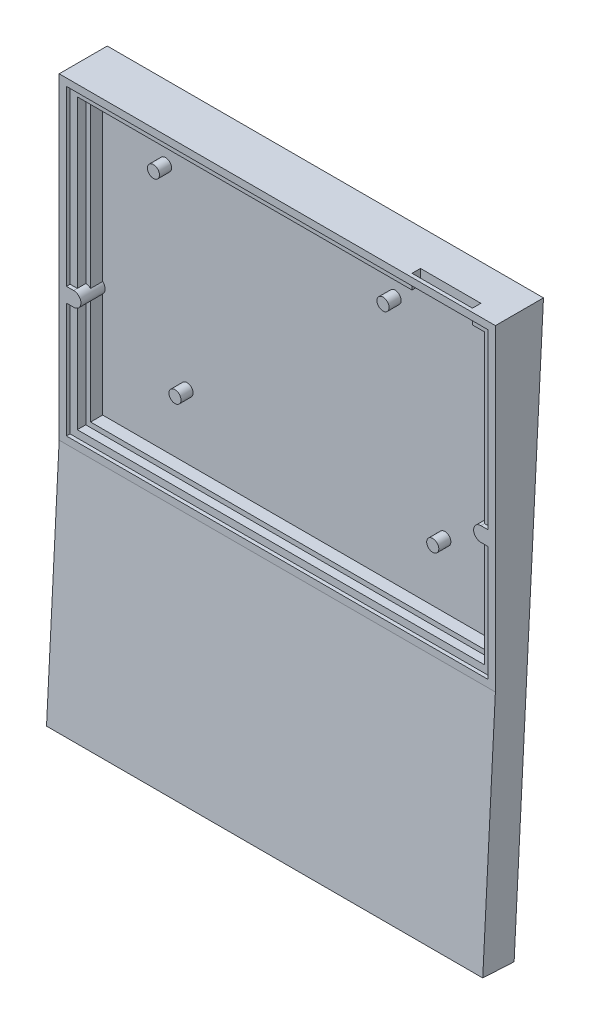
SolidWorks part; units mm, degrees
ref_plane "前视基准面" through (0, 0, 0) normal (0, 0, 1) x (1, 0, 0)
ref_plane "上视基准面" through (0, 0, 0) normal (0, 1, 0) x (1, 0, 0)
ref_plane "右视基准面" through (0, 0, 0) normal (1, 0, 0) x (0, 0, -1)
sketch "Model" plane through (0, 0, 0) normal (0, 0, 1) x (1, 0, 0)
  line L0 (565.3976, -76.1053) -> (390.8957, -76.1053)
  line L1 (390.8957, -76.1053) -> (390.8957, -28.4789)
  line L2 (390.8957, -22.4789) -> (390.8957, 49.195)
  line L3 (390.8957, 49.195) -> (565.3976, 49.195)
  line L4 (390.8957, -22.4789) -> (393.8957, -22.4789)
  line L5 (390.8957, -28.4789) -> (393.8957, -28.4789)
  line L6 (565.3976, -22.4796) -> (562.3976, -22.4796)
  line L7 (565.3976, -28.4796) -> (562.3976, -28.4796)
  line L8 (565.3976, 49.195) -> (565.3976, -22.4796)
  line L9 (565.3976, -28.4796) -> (565.3976, -76.1053)
  line L10 (562.3976, 46.195) -> (562.3976, -22.4796)
  line L11 (393.8957, -22.4789) -> (393.8957, 46.195)
  line L12 (393.8957, 46.195) -> (562.3976, 46.195)
  line L13 (393.8957, -73.1053) -> (393.8957, -28.4789)
  line L14 (562.3976, -73.1053) -> (393.8957, -73.1053)
  line L15 (562.3976, -28.4796) -> (562.3976, -73.1053)
  line L16 (387.8957, -79.1053) -> (387.8957, 52.195)
  line L17 (387.8957, 52.195) -> (568.3976, 52.195)
  line L18 (568.3976, 52.195) -> (568.3976, -79.1053)
  line L19 (568.3976, -79.1053) -> (387.8957, -79.1053)
  line L20 (560.3976, -71.1053) -> (395.8957, -71.1053)
  line L21 (395.8957, -71.1053) -> (395.8957, -27.715)
  line L22 (560.3976, -27.7157) -> (560.3976, -71.1053)
  line L23 (560.3976, 44.195) -> (560.3976, -23.2435)
  line L24 (395.8957, -23.2428) -> (395.8957, 44.195)
  line L25 (395.8957, 44.195) -> (560.3976, 44.195)
  line L26 (393.8957, -22.4789) -> (390.8957, -22.4789)
  line L27 (390.8957, 49.195) -> (565.3976, 49.195)
  line L28 (565.3976, -22.4796) -> (562.3976, -22.4796)
  line L29 (562.3976, 46.195) -> (393.8957, 46.195)
  arc A0 (393.8957, -28.4789) -> (393.8957, -22.4789) centre (393.8957, -25.4789) ccw
  arc A1 (562.3976, -22.4796) -> (562.3976, -28.4796) centre (562.3976, -25.4796) ccw
extrude "凸台-拉伸3" add sketch "Model" along normal blind 8.5 contours L7 L15 L14 L13 L5 L1 L0 L9 | L11 L12 L10 L6 L8 L3 L2 L4
sketch "草图4" plane through (0, 0, 0) normal (0, 0, -1) x (-1, 0, 0)
  line L0 (-568.3976, -79.1053) -> (-568.3976, 52.195)
  line L1 (-568.3976, 52.195) -> (-387.8957, 52.195)
  line L2 (-387.8957, 52.195) -> (-387.8957, -79.1053)
  line L3 (-387.8957, -79.1053) -> (-568.3976, -79.1053)
  line L4 (-390.8957, -76.1053) -> (-565.3976, -76.1053)
  line L5 (-565.3976, -76.1053) -> (-565.3976, -28.4796)
  line L6 (-565.3976, -28.4796) -> (-562.3976, -28.4796)
  line L7 (-562.3976, -22.4796) -> (-565.3976, -22.4796)
  line L8 (-565.3976, -22.4796) -> (-565.3976, 49.195)
  line L9 (-565.3976, 49.195) -> (-390.8957, 49.195)
  line L10 (-390.8957, 49.195) -> (-390.8957, -22.4789)
  line L11 (-390.8957, -22.4789) -> (-393.8957, -22.4789)
  line L12 (-393.8957, -28.4789) -> (-390.8957, -28.4789)
  line L13 (-390.8957, -28.4789) -> (-390.8957, -76.1053)
  line L14 (-393.8957, -73.1053) -> (-393.8957, -28.4789) construction
  arc A0 (-393.8957, -22.4789) -> (-393.8957, -28.4789) centre (-393.8957, -25.4789) ccw
  arc A1 (-562.3976, -28.4796) -> (-562.3976, -22.4796) centre (-562.3976, -25.4796) ccw
  arc A2 (-562.3976, -28.4796) -> (-562.3976, -22.4796) centre (-562.3976, -25.4796) ccw construction
  line M5 (-562.3976, -28.4796) -> (-565.3976, -28.4796)
  line M6 (-565.3976, -28.4796) -> (-565.3976, -76.1053)
  line M7 (-565.3976, -76.1053) -> (-390.8957, -76.1053)
  line M8 (-390.8957, -76.1053) -> (-390.8957, -28.4789)
  line M9 (-390.8957, -28.4789) -> (-393.8957, -28.4789)
extrude "凸台-拉伸5" add sketch "草图4" against normal blind 10 contours L3 L2 L1 L0 A1 L7 L8 L9 L10 L11 A0 M5 M9 M8 M7 M6
sketch "草图5" plane through (0, 0, 0) normal (0, 0, -1) x (-1, 0, 0)
  line L0 (-562.3976, -22.4796) -> (-562.3976, 46.195)
  line L1 (-562.3976, 46.195) -> (-393.8957, 46.195)
  line L2 (-393.8957, 46.195) -> (-393.8957, -22.4789)
  line L3 (-395.8957, -23.2428) -> (-395.8957, 44.195)
  line L4 (-395.8957, 44.195) -> (-560.3976, 44.195)
  line L5 (-560.3976, 44.195) -> (-560.3976, -23.2435)
  line L6 (-560.3976, -27.7157) -> (-560.3976, -71.1053)
  line L7 (-560.3976, -71.1053) -> (-395.8957, -71.1053)
  line L8 (-395.8957, -71.1053) -> (-395.8957, -27.715)
  line L9 (-393.8957, -28.4789) -> (-393.8957, -73.1053)
  line L10 (-393.8957, -73.1053) -> (-562.3976, -73.1053)
  line L11 (-562.3976, -73.1053) -> (-562.3976, -28.4796)
  arc A0 (-562.3976, -22.4796) -> (-560.3976, -23.2435) centre (-562.3976, -25.4796) cw
  arc A1 (-562.3976, -28.4796) -> (-560.3976, -27.7157) centre (-562.3976, -25.4796) ccw
  arc A2 (-393.8957, -28.4789) -> (-395.8957, -27.715) centre (-393.8957, -25.4789) cw
  arc A3 (-395.8957, -23.2428) -> (-393.8957, -22.4789) centre (-393.8957, -25.4789) cw
  arc A4 (-393.8957, -22.4789) -> (-393.8957, -28.4789) centre (-393.8957, -25.4789) ccw construction
  line M1 (-393.8957, 46.195) -> (-393.8957, -22.4789)
  arc M2 (-393.8957, -22.4789) -> (-393.8957, -28.4789) centre (-393.8957, -25.4789) ccw
  line M3 (-393.8957, -28.4789) -> (-393.8957, -73.1053)
  line M4 (-393.8957, -73.1053) -> (-562.3976, -73.1053)
  line M5 (-562.3976, -73.1053) -> (-562.3976, -28.4796)
  arc M6 (-562.3976, -28.4796) -> (-562.3976, -22.4796) centre (-562.3976, -25.4796) ccw
  line M7 (-562.3976, -22.4796) -> (-562.3976, 46.195)
  line M8 (-562.3976, 46.195) -> (-393.8957, 46.195)
extrude "凸台-拉伸6" add sketch "草图5" against normal blind 5 contours L5 L4 L3 M2 M1 M8 M7 M6 | L8 L7 L6 M6 M5 M4 M3 M2
sketch "草图8" plane through (0, 0, 5) normal (0, 0, 1) x (1, 0, 0)
  line L0 (393.8957, 46.195) -> (562.3976, 46.195) construction
  line L1 (557.3976, 46.195) -> (532.3976, 46.195)
  line L2 (557.3976, 46.195) -> (557.3976, 52.195)
  line L3 (557.3976, 52.195) -> (532.3976, 52.195)
  line L4 (532.3976, 46.195) -> (532.3976, 52.195)
  line L5 (568.3976, 52.195) -> (387.8957, 52.195) construction
  dimension "D1" = 5
  dimension "D2" = 25
extrude "切除-拉伸1" cut sketch "草图8" along normal blind 3.5
sketch "草图9" plane through (0, 0, 0) normal (0, 0, -1) x (-1, 0, 0)
  line L0 (-393.8957, 46.195) -> (-562.3976, 46.195) construction
  circle A0 centre (-430.8057, -44.5253) radius 2.5
  circle A1 centre (-537.4776, -44.5253) radius 2.5
  circle A2 centre (-421.8957, 31.665) radius 2.5
  circle A3 centre (-516.8957, 31.665) radius 2.5
  dimension "D1" = 36.91
  dimension "D2" = 28.58
  dimension "D3" = 24.92
  dimension "D4" = 28.58
  dimension "D5" = 95
  dimension "D6" = 28
  dimension "D7" = 14.53
  dimension "D8" = 14.53
extrude "凸台-拉伸7" add sketch "草图9" against normal blind 5 separate body
sketch "草图10" plane through (387.8957, 0, 0) normal (-1, 0, 0) x (0, 0, 1)
  line L2 (2.2514, -179.6486) -> (-9.899, 52.195)
  line L3 (10, -79.1053) -> (0, -79.1053)
  line L4 (0, -79.1053) -> (0, 52.195)
  line L5 (0, 52.195) -> (-9.899, 52.195)
  line L6 (2.2514, -179.6486) -> (15.2336, -178.9683)
  line L7 (15.2336, -178.9683) -> (10, -79.1053)
  dimension "D1" = 13
  dimension "D2" = 3
  dimension "D3" = 100
extrude "凸台-拉伸8" add sketch "草图10" against normal up to surface (180.5019 mm away) up to face at (568.3976, -13.4551, 5)
